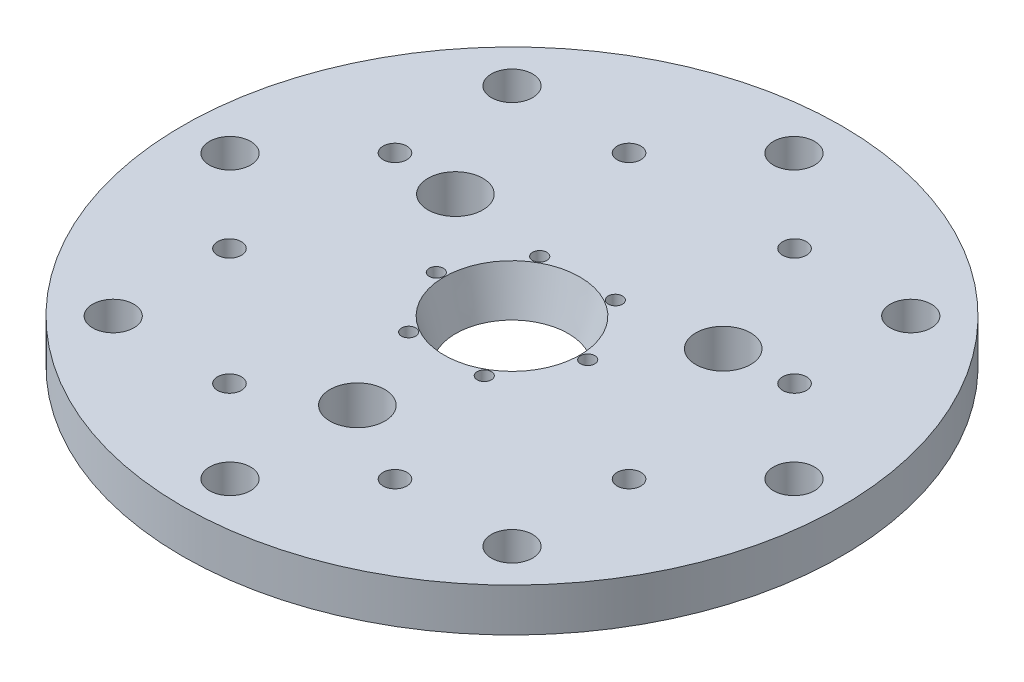
SolidWorks part; units mm, degrees
material "AISI 1020"
ref_plane "Front Plane" through (0, 0, 0) normal (0, 0, 1) x (1, 0, 0)
ref_plane "Top Plane" through (0, 0, 0) normal (0, 1, 0) x (1, 0, 0)
ref_plane "Right Plane" through (0, 0, 0) normal (1, 0, 0) x (0, 0, -1)
sketch "Sketch1" plane through (0, 0, 0) normal (0, 1, 0) x (1, 0, 0)
  circle A0 centre (0, 0) radius 76.2
  dimension "D1" = 152.4
extrude "Boss-Extrude1" add sketch "Sketch1" along normal blind 10 contours A0
sketch "Sketch5" plane through (0, 0, 0) normal (0, 0, 1) x (1, 0, 0)
  line L0 (0, 0) -> (0, 29.9809) construction
  line L1 (0, 0) -> (0, 10)
  line L2 (13, 0) -> (15.6795, 10)
  line L4 (76.2, 10) -> (-76.2, 10) construction
  line L6 (-76.2, 0) -> (76.2, 0) construction
  line L7 (0, 0) -> (13, 0)
  line L8 (15.6795, 10) -> (0, 10)
  line L9 (13, 0) -> (13, 10) construction
  dimension "D1" = 13
  dimension "D3" = 15
revolve "Cut-Revolve1" cut sketch "Sketch5" angle 360 about L0
sketch "Sketch6" plane through (0, 0, 0) normal (0, 1, 0) x (1, 0, 0)
  line L0 (0, 0) -> (46.194, 19.1342) construction
  line L1 (0, 0) -> (76.2, 0) construction
  circle A0 centre (46.194, 19.1342) radius 2.75
  circle A1 centre (0, 0) radius 76.2 construction
  dimension "D1" = 5.5
  dimension "D2" = 50
  dimension "D3" = 22.5
extrude "Cut-Extrude3" cut sketch "Sketch6" along normal through all
pattern_circular "CirPattern1" count 8 over 360 about axis through (0, 0, 0) along (0, 1, 0) of "Cut-Extrude3"
sketch "Sketch7" plane through (0, 10, 0) normal (0, 1, 0) x (1, 0, 0)
  line L0 (0, 0) -> (30.9604, 17.875) construction
  line L1 (0, 0) -> (54.5383, 0) construction
  circle A0 centre (30.9604, 17.875) radius 6.35
  dimension "D1" = 12.7
  dimension "D2" = 35.75
  dimension "D3" = 30
extrude "Cut-Extrude4" cut sketch "Sketch7" against normal through all
cosmetic thread "Cosmetic Thread2" parameters "D2"=14.2875
pattern_circular "CirPattern2" count 3 over 360 about axis through (0, 0, 0) along (0, 1, 0) of "Cut-Extrude4"
cosmetic thread "Cosmetic Thread1" parameters "D2"=14.2875
cosmetic thread "Cosmetic Thread3" parameters "D2"=14.2875
cosmetic thread "Cosmetic Thread4" parameters "D2"=14.2875
sketch "Sketch8" plane through (0, 10, 0) normal (0, 1, 0) x (1, 0, 0)
  line L0 (0, 0) -> (17.5, 0) construction
  dimension "D1" = 17.5
sketch "Sketch9" plane through (0, 10, 0) normal (0, 1, 0) x (1, 0, 0)
  circle A0 centre (0, 0) radius 65.2 construction
  dimension "D1" = 130.4
hole_wizard "3/8 (0.375) Diameter Hole1" positions "Sketch10" profile "Sketch11" hole size "3/8" standard "ANSI Inch" end condition through all
sketch "Sketch10" plane through (0, 10, 0) normal (0, 1, 0) x (1, 0, 0)
  circle A0 centre (0, 0) radius 65.2 construction
  point P0 (-65.2, 0)
sketch "Sketch11" plane through (-65.2, 10, 0) normal (1, 0, 0) x (0, 0, 1)
  line L0 (0, 0) -> (0, 10)
  line L1 (0, 10) -> (4.7625, 10)
  line L2 (4.7625, 10) -> (4.7625, 0)
  line L5 (4.7625, 0) -> (0, 0)
  line L11 (0, -6.35) -> (0, 107.95) construction
  dimension "Thru Hole Dia." = 9.525
  dimension "Thru Hole Depth" = 10
pattern_circular "CirPattern4" count 8 over 360 about axis through (0, 0, 0) along (0, 1, 0) of "3/8 (0.375) Diameter Hole1"
hole_wizard "Tap Drill for M4x0.7 Tap1" positions "Sketch12" profile "Sketch13" hole size "M4x0.7" standard "ANSI Metric"
sketch "Sketch12" plane through (0, 10, 0) normal (0, 1, 0) x (1, 0, 0)
  point P0 (17.5, 0)
sketch "Sketch13" plane through (17.5, 10, 0) normal (1, 0, 0) x (0, 0, 1)
  line L0 (0, 0) -> (0, 8.9914)
  line L1 (0, 8.9914) -> (1.65, 8)
  line L2 (1.65, 8) -> (1.65, 0)
  line L5 (1.65, 0) -> (0, 0)
  line L10 (0, 8.9914) -> (-1.65, 8) construction
  line L11 (0, -6.35) -> (0, 107.95) construction
  dimension "Hole Dia." = 3.3
  dimension "Hole Depth" = 8
  dimension "Drill Angle" = 118
cosmetic thread "Cosmetic Thread5" parameters "D2"=4.1656
pattern_circular "CirPattern5" count 6 over 360 about axis through (0, 0, 0) along (0, 1, 0) of "Tap Drill for M4x0.7 Tap1"
cosmetic thread "Cosmetic Thread6" parameters "D2"=4.1656
cosmetic thread "Cosmetic Thread7" parameters "D2"=4.1656
cosmetic thread "Cosmetic Thread8" parameters "D2"=4.1656
cosmetic thread "Cosmetic Thread9" parameters "D2"=4.1656
cosmetic thread "Cosmetic Thread10" parameters "D2"=4.1656
